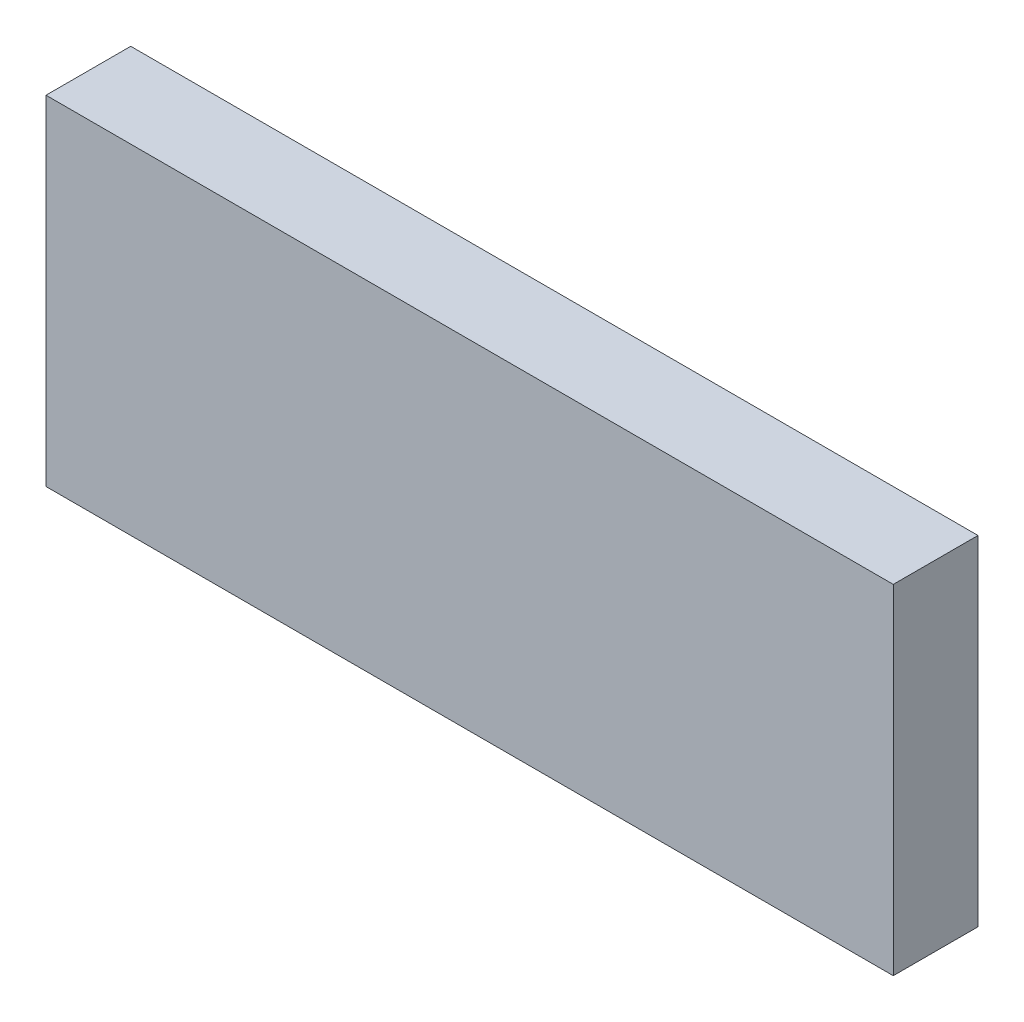
SolidWorks part; units mm, degrees
ref_plane "前视基准面" through (0, 0, 0) normal (0, 0, 1) x (1, 0, 0)
ref_plane "上视基准面" through (0, 0, 0) normal (0, 1, 0) x (1, 0, 0)
ref_plane "右视基准面" through (0, 0, 0) normal (1, 0, 0) x (0, 0, -1)
other "Configuration Table"
sketch "草图1" plane through (0, 0, 0) normal (0, 0, 1) x (1, 0, 0)
  line L1 (-50, -20) -> (50, -20)
  line L2 (-50, -20) -> (-50, 20)
  line L3 (-50, 20) -> (50, 20)
  line L4 (50, -20) -> (50, 20)
  line L5 (-50, -20) -> (50, 20) construction
  line L6 (-50, 20) -> (50, -20) construction
  point P0 (0, 0)
extrude "凸台-拉伸1" add sketch "草图1" along normal blind 10
